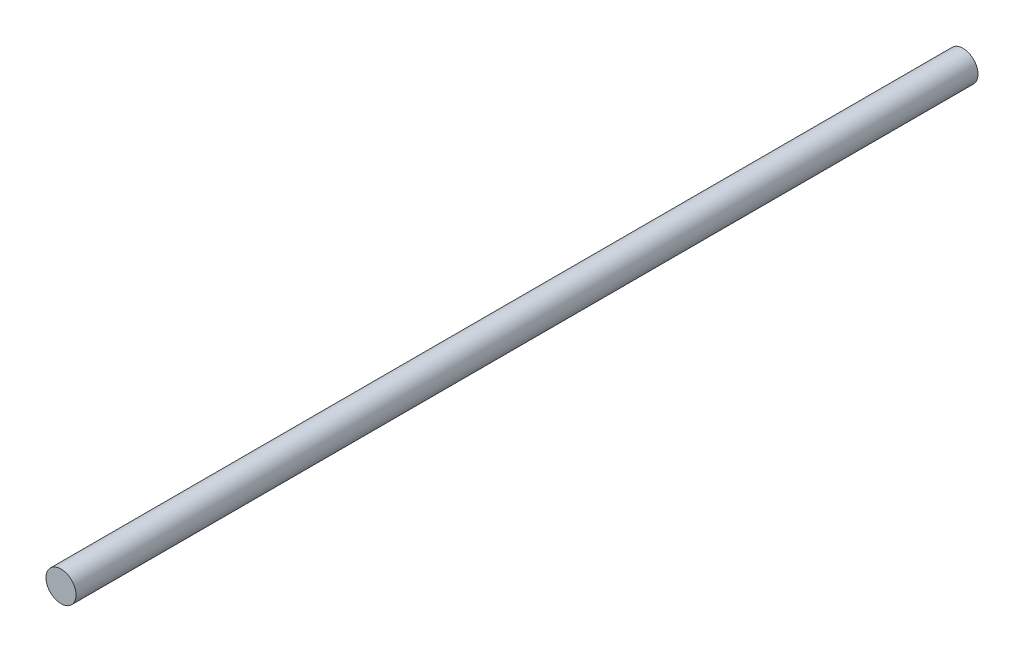
SolidWorks part; units mm, degrees
ref_plane "Plan de face" through (0, 0, 0) normal (0, 0, 1) x (1, 0, 0)
ref_plane "Plan de dessus" through (0, 0, 0) normal (0, 1, 0) x (1, 0, 0)
ref_plane "Plan de droite" through (0, 0, 0) normal (1, 0, 0) x (0, 0, -1)
sketch "Esquisse1" plane through (0, 0, 0) normal (0, 0, 1) x (1, 0, 0)
  circle A0 centre (0, 0) radius 2.5
  dimension "D1" = 5
extrude "Boss.-Extru.1" add sketch "Esquisse1" along normal blind 150
